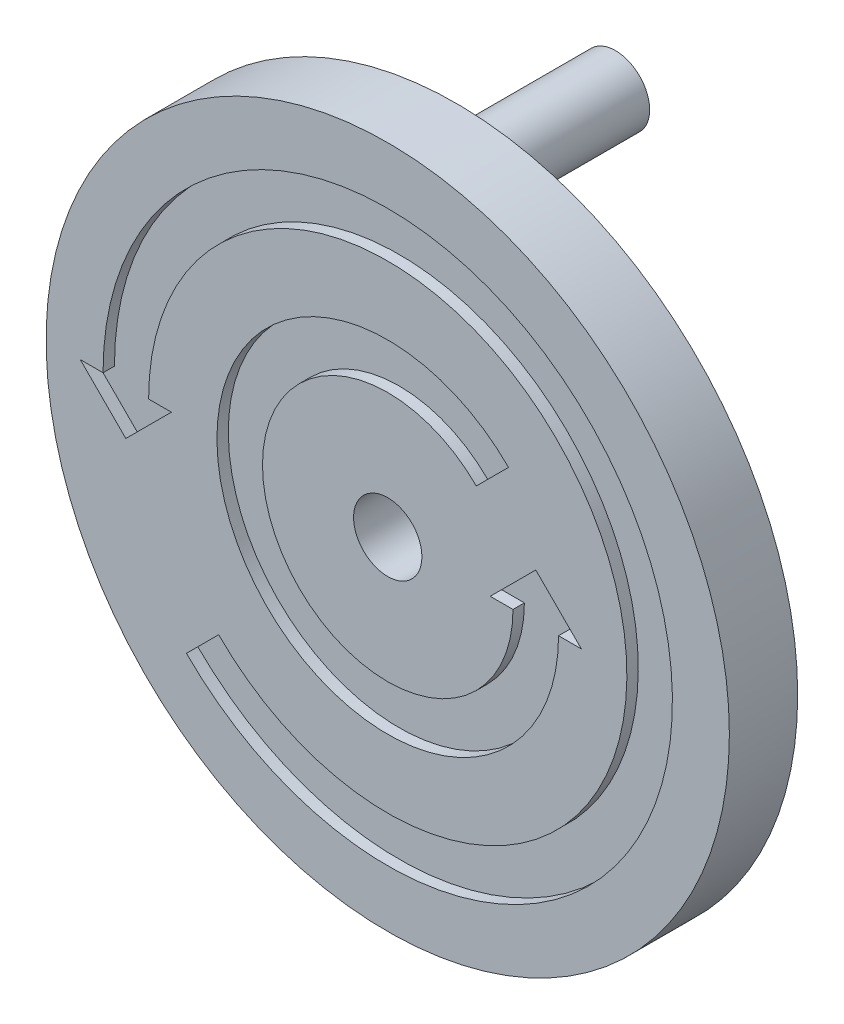
SolidWorks part; units mm, degrees
ref_plane "Alzado" through (0, 0, 0) normal (0, 0, 1) x (1, 0, 0)
ref_plane "Planta" through (0, 0, 0) normal (0, 1, 0) x (1, 0, 0)
ref_plane "Vista lateral" through (0, 0, 0) normal (1, 0, 0) x (0, 0, -1)
sketch "Croquis1" plane through (0, 0, 0) normal (0, 0, 1) x (1, 0, 0)
  circle A0 centre (0, 0) radius 15
  circle A1 centre (0, 12) radius 1.5
  circle A2 centre (0, -12) radius 1.5
  circle A3 centre (0, 0) radius 1.5
  dimension "D1" = 30
  dimension "D2" = 3
  dimension "D3" = 3
  dimension "D6" = 3
  dimension "D4" = 12
  dimension "D5" = 24
extrude "Saliente-Extruir1" add sketch "Croquis1" along normal blind 3
sketch "Croquis2" plane through (0, 0, 3) normal (0, 0, 1) x (1, 0, 0)
  circle A0 centre (0, -12) radius 1.5 construction
  circle A1 centre (0, 12) radius 1.5 construction
  circle A3 centre (0, -12) radius 1.5
  circle A4 centre (0, 12) radius 1.5
extrude "Saliente-Extruir2" add sketch "Croquis2" against normal blind 10
sketch "Croquis3" plane through (0, 0, 3) normal (0, 0, 1) x (1, 0, 0)
  line L0 (-7.4246, -7.4246) -> (-8.8388, -8.8388)
  line L1 (0, 0) -> (-7.4246, -7.4246) construction
  line L2 (-12.5, 0) -> (-13.5, 0)
  line L3 (-13.5, 0) -> (-11.5, -2)
  line L4 (-11.5, -2) -> (-9.5, 0)
  line L5 (-9.5, 0) -> (-10.5, 0)
  line L6 (-12.5, 0) -> (-10.5, 0) construction
  line L7 (5.5, 0) -> (4.5, 0)
  line L8 (4.5, 0) -> (6.5, 2)
  line L9 (6.5, 2) -> (8.5, 0)
  line L10 (8.5, 0) -> (7.5, 0)
  line L11 (5.5, 0) -> (7.5, 0) construction
  line L12 (3.8891, 3.8891) -> (5.3033, 5.3033)
  line L13 (0, 0) -> (3.8891, 3.8891) construction
  arc A0 (-8.8388, -8.8388) -> (-12.5, 0) centre (0, 0) ccw
  arc A1 (-7.4246, -7.4246) -> (-10.5, 0) centre (0, 0) ccw
  arc A2 (-12.5, 0) -> (-12.4564, -1.0436) centre (0, 0) ccw construction
  arc A3 (-10.5, 0) -> (-10.4564, -0.9564) centre (0, 0) ccw construction
  arc A4 (-10.4564, -0.9564) -> (-7.4246, -7.4246) centre (0, 0) ccw construction
  arc A5 (-12.4564, -1.0436) -> (-8.8388, -8.8388) centre (0, 0) ccw construction
  arc A6 (5.3033, 5.3033) -> (7.5, 0) centre (0, 0) ccw
  arc A7 (3.8891, 3.8891) -> (5.5, 0) centre (0, 0) ccw
  arc A8 (5.5, 0) -> (5.4221, 0.9221) centre (0, 0) ccw construction
  arc A9 (7.5, 0) -> (7.4221, 1.0779) centre (0, 0) ccw construction
  arc A10 (5.4221, 0.9221) -> (3.8891, 3.8891) centre (0, 0) ccw construction
  arc A11 (7.4221, 1.0779) -> (5.3033, 5.3033) centre (0, 0) ccw construction
  point P8 (-11.5, 0)
  point P16 (6.5, 0)
  dimension "D1" = 25
  dimension "D2" = 21
  dimension "D7" = 15
  dimension "D8" = 11
  dimension "D3" = 2
  dimension "D4" = 4
  dimension "D5" = 2
  dimension "D6" = 45
  dimension "D9" = 4
  dimension "D10" = 2
  dimension "D11" = 2
extrude "Cortar-Extruir1" cut sketch "Croquis3" against normal blind 0.5
